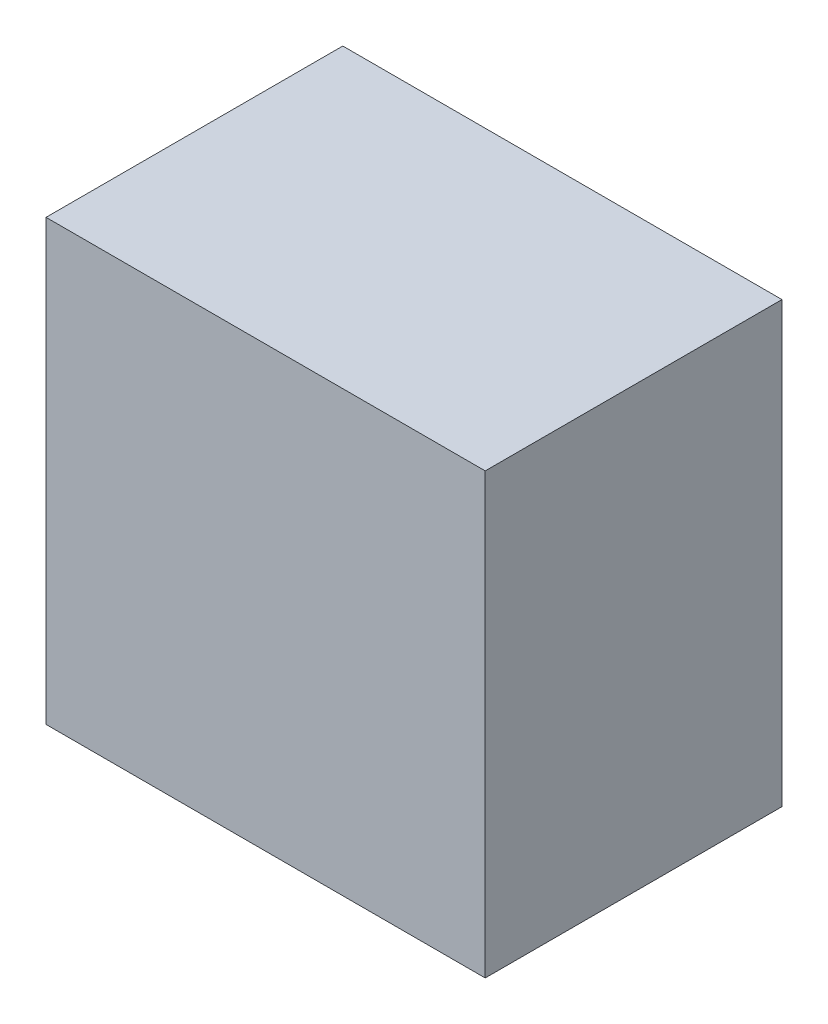
SolidWorks part; units mm, degrees
ref_plane "前视基准面" through (0, 0, 0) normal (0, 0, 1) x (1, 0, 0)
ref_plane "上视基准面" through (0, 0, 0) normal (0, 1, 0) x (1, 0, 0)
ref_plane "右视基准面" through (0, 0, 0) normal (1, 0, 0) x (0, 0, -1)
other "Configuration Table"
sketch "Reference_back_bounds_37x37" plane through (0, 0, 0) normal (0, 0, 1) x (1, 0, 0)
  line L1 (-18.5, -18.5) -> (18.5, -18.5)
  line L2 (-18.5, -18.5) -> (-18.5, 18.5)
  line L3 (-18.5, 18.5) -> (18.5, 18.5)
  line L4 (18.5, -18.5) -> (18.5, 18.5)
extrude "Rear25_CLEARANCE_ENVELOPE_NOT_REAL_SHAPE" add sketch "Reference_back_bounds_37x37" along normal blind 25
